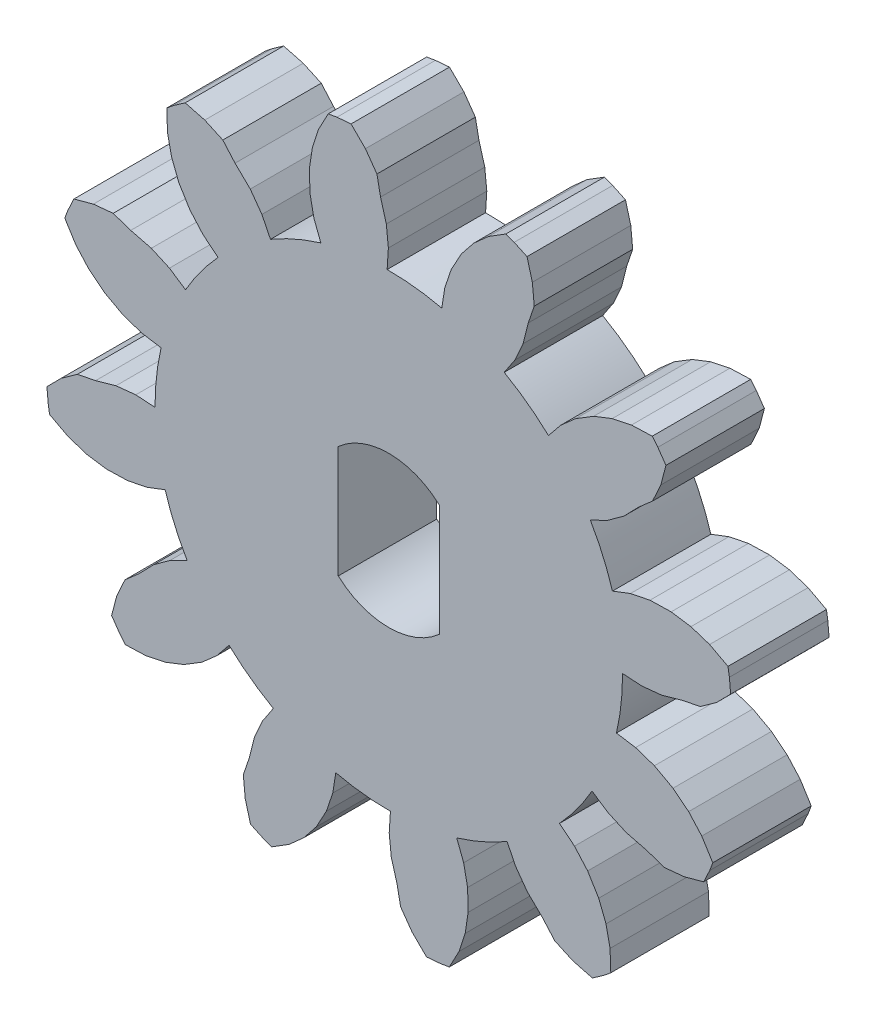
SolidWorks part; units mm, degrees
ref_plane "Front Plane" through (0, 0, 0) normal (0, 0, 1) x (1, 0, 0)
ref_plane "Top Plane" through (0, 0, 0) normal (0, 1, 0) x (1, 0, 0)
ref_plane "Right Plane" through (0, 0, 0) normal (1, 0, 0) x (0, 0, -1)
sketch "Sketch2" plane through (0, 0, 0) normal (0, 0, 1) x (1, 0, 0)
  line L0 (10.7643, 2.769) -> (11.3146, 2.9798)
  line L1 (11.3146, 2.9798) -> (11.9079, 3.1)
  line L2 (11.9079, 3.1) -> (12.5541, 3.1166)
  line L3 (12.5541, 3.1166) -> (13.1558, 3.0264)
  line L4 (13.1558, 3.0264) -> (13.7249, 2.84)
  line L5 (13.7249, 2.84) -> (14.2846, 2.5428)
  line L6 (14.2846, 2.5428) -> (14.3284, 2.2778)
  line L7 (10.8865, -0.9167) -> (11.4685, -1.0092)
  line L8 (14.3655, 1.8481) -> (14.3284, 2.2778)
  line L9 (13.9315, 1.41) -> (14.3655, 1.8481)
  line L10 (13.4388, 1.0592) -> (13.9315, 1.41)
  line L11 (12.8839, 0.949) -> (13.4388, 1.0592)
  line L12 (12.2621, 0.7727) -> (12.8839, 0.949)
  line L13 (11.6599, 0.7109) -> (12.2621, 0.7727)
  line L14 (11.0718, 0.7486) -> (11.6599, 0.7109)
  line L15 (11.4685, -1.0092) -> (12.0424, -1.2018)
  line L16 (12.0424, -1.2018) -> (12.6103, -1.5105)
  line L17 (12.6103, -1.5105) -> (13.0864, -1.8894)
  line L18 (13.0864, -1.8894) -> (13.486, -2.3355)
  line L19 (13.486, -2.3355) -> (13.8222, -2.8726)
  line L20 (13.8222, -2.8726) -> (13.7276, -3.1241)
  line L21 (13.5448, -3.5148) -> (13.7276, -3.1241)
  line L22 (12.9499, -3.6771) -> (13.5448, -3.5148)
  line L23 (12.3478, -3.7346) -> (12.9499, -3.6771)
  line L24 (11.8122, -3.5526) -> (12.3478, -3.7346)
  line L25 (11.1855, -3.3943) -> (11.8122, -3.5526)
  line L26 (10.6331, -3.1467) -> (11.1855, -3.3943)
  line L27 (10.1426, -2.8201) -> (10.6331, -3.1467)
  line L28 (9.1496, -4.1696) -> (9.6073, -4.5407)
  line L29 (9.6073, -4.5407) -> (10.008, -4.9945)
  line L30 (10.008, -4.9945) -> (10.3455, -5.5458)
  line L31 (10.3455, -5.5458) -> (10.5683, -6.112)
  line L32 (10.5683, -6.112) -> (10.6914, -6.6981)
  line L33 (10.6914, -6.6981) -> (10.7139, -7.3314)
  line L34 (10.7139, -7.3314) -> (10.5062, -7.5019)
  line L35 (10.1526, -7.7488) -> (10.5062, -7.5019)
  line L36 (9.5562, -7.5919) -> (10.1526, -7.7488)
  line L37 (9.0061, -7.3406) -> (9.5562, -7.5919)
  line L38 (8.6333, -6.9152) -> (9.0061, -7.3406)
  line L39 (8.1696, -6.4648) -> (8.6333, -6.9152)
  line L40 (7.815, -5.9742) -> (8.1696, -6.4648)
  line L41 (7.5536, -5.4461) -> (7.815, -5.9742)
  line L42 (6.0188, -6.1183) -> (6.2297, -6.6686)
  line L43 (6.2297, -6.6686) -> (6.3499, -7.2619)
  line L44 (6.3499, -7.2619) -> (6.3665, -7.908)
  line L45 (6.3665, -7.908) -> (6.2763, -8.5098)
  line L46 (6.2763, -8.5098) -> (6.0898, -9.0789)
  line L47 (6.0898, -9.0789) -> (5.7927, -9.6386)
  line L48 (5.7927, -9.6386) -> (5.5276, -9.6824)
  line L49 (5.098, -9.7194) -> (5.5276, -9.6824)
  line L50 (4.6599, -9.2854) -> (5.098, -9.7194)
  line L51 (4.3091, -8.7928) -> (4.6599, -9.2854)
  line L52 (4.1989, -8.2379) -> (4.3091, -8.7928)
  line L53 (4.0226, -7.616) -> (4.1989, -8.2379)
  line L54 (3.9608, -7.0138) -> (4.0226, -7.616)
  line L55 (3.9984, -6.4257) -> (3.9608, -7.0138)
  line L56 (2.3332, -6.2405) -> (2.2407, -6.8225)
  line L57 (2.2407, -6.8225) -> (2.0481, -7.3964)
  line L58 (2.0481, -7.3964) -> (1.7394, -7.9643)
  line L59 (1.7394, -7.9643) -> (1.3604, -8.4404)
  line L60 (1.3604, -8.4404) -> (0.9144, -8.84)
  line L61 (0.9144, -8.84) -> (0.3772, -9.1761)
  line L62 (0.3772, -9.1761) -> (0.1257, -9.0815)
  line L63 (-0.2649, -8.8988) -> (0.1257, -9.0815)
  line L64 (-0.4273, -8.3038) -> (-0.2649, -8.8988)
  line L65 (-0.4847, -7.7018) -> (-0.4273, -8.3038)
  line L66 (-0.3027, -7.1662) -> (-0.4847, -7.7018)
  line L67 (-0.1445, -6.5395) -> (-0.3027, -7.1662)
  line L68 (0.1031, -5.9871) -> (-0.1445, -6.5395)
  line L69 (0.4298, -5.4966) -> (0.1031, -5.9871)
  line L70 (-0.9197, -4.5036) -> (-1.2909, -4.9613)
  line L71 (-1.2909, -4.9613) -> (-1.7446, -5.362)
  line L72 (-1.7446, -5.362) -> (-2.2959, -5.6995)
  line L73 (-2.2959, -5.6995) -> (-2.8621, -5.9223)
  line L74 (-2.8621, -5.9223) -> (-3.4482, -6.0454)
  line L75 (-3.4482, -6.0454) -> (-4.0815, -6.0679)
  line L76 (-4.0815, -6.0679) -> (-4.252, -5.8602)
  line L77 (-4.4989, -5.5066) -> (-4.252, -5.8602)
  line L78 (-4.3421, -4.9102) -> (-4.4989, -5.5066)
  line L79 (-4.0908, -4.3601) -> (-4.3421, -4.9102)
  line L80 (-3.6654, -3.9872) -> (-4.0908, -4.3601)
  line L81 (-3.215, -3.5236) -> (-3.6654, -3.9872)
  line L82 (-2.7243, -3.169) -> (-3.215, -3.5236)
  line L83 (-2.1962, -2.9076) -> (-2.7243, -3.169)
  line L84 (-2.8684, -1.3728) -> (-3.4187, -1.5837)
  line L85 (-3.4187, -1.5837) -> (-4.012, -1.7038)
  line L86 (-4.012, -1.7038) -> (-4.6582, -1.7205)
  line L87 (-4.6582, -1.7205) -> (-5.2599, -1.6303)
  line L88 (-5.2599, -1.6303) -> (-5.829, -1.4438)
  line L89 (-5.829, -1.4438) -> (-6.3887, -1.1467)
  line L90 (-6.3887, -1.1467) -> (-6.4325, -0.8816)
  line L91 (-6.4696, -0.4519) -> (-6.4325, -0.8816)
  line L92 (-6.0356, -0.0138) -> (-6.4696, -0.4519)
  line L93 (-5.5429, 0.3369) -> (-6.0356, -0.0138)
  line L94 (-4.988, 0.4471) -> (-5.5429, 0.3369)
  line L95 (-4.3662, 0.6234) -> (-4.988, 0.4471)
  line L96 (-3.764, 0.6852) -> (-4.3662, 0.6234)
  line L97 (-3.1759, 0.6476) -> (-3.764, 0.6852)
  line L98 (-2.9906, 2.3128) -> (-3.5726, 2.4053)
  line L99 (-3.5726, 2.4053) -> (-4.1465, 2.5979)
  line L100 (-4.1465, 2.5979) -> (-4.7144, 2.9066)
  line L101 (-4.7144, 2.9066) -> (-5.1905, 3.2856)
  line L102 (-5.1905, 3.2856) -> (-5.5901, 3.7316)
  line L103 (-5.5901, 3.7316) -> (-5.9263, 4.2688)
  line L104 (-5.9263, 4.2688) -> (-5.8317, 4.5203)
  line L105 (-5.6489, 4.9109) -> (-5.8317, 4.5203)
  line L106 (-5.054, 5.0733) -> (-5.6489, 4.9109)
  line L107 (-4.4519, 5.1307) -> (-5.054, 5.0733)
  line L108 (-3.9163, 4.9487) -> (-4.4519, 5.1307)
  line L109 (-3.2896, 4.7905) -> (-3.9163, 4.9487)
  line L110 (-2.7372, 4.5429) -> (-3.2896, 4.7905)
  line L111 (-2.2467, 4.2163) -> (-2.7372, 4.5429)
  line L112 (-1.2537, 5.5658) -> (-1.7114, 5.9369)
  line L113 (-1.7114, 5.9369) -> (-2.1121, 6.3906)
  line L114 (-2.1121, 6.3906) -> (-2.4496, 6.9419)
  line L115 (-2.4496, 6.9419) -> (-2.6724, 7.5081)
  line L116 (-2.6724, 7.5081) -> (-2.7955, 8.0942)
  line L117 (-2.7955, 8.0942) -> (-2.818, 8.7275)
  line L118 (-2.818, 8.7275) -> (-2.6103, 8.898)
  line L119 (-2.2567, 9.1449) -> (-2.6103, 8.898)
  line L120 (-1.6603, 8.9881) -> (-2.2567, 9.1449)
  line L121 (-1.1102, 8.7368) -> (-1.6603, 8.9881)
  line L122 (-0.7374, 8.3114) -> (-1.1102, 8.7368)
  line L123 (-0.2737, 7.861) -> (-0.7374, 8.3114)
  line L124 (0.0809, 7.3703) -> (-0.2737, 7.861)
  line L125 (0.3423, 6.8422) -> (0.0809, 7.3703)
  line L126 (1.8771, 7.5144) -> (1.6662, 8.0647)
  line L127 (1.6662, 8.0647) -> (1.546, 8.658)
  line L128 (1.546, 8.658) -> (1.5294, 9.3042)
  line L129 (1.5294, 9.3042) -> (1.6196, 9.906)
  line L130 (1.6196, 9.906) -> (1.8061, 10.4751)
  line L131 (1.8061, 10.4751) -> (2.1032, 11.0347)
  line L132 (2.1032, 11.0347) -> (2.3683, 11.0786)
  line L133 (2.798, 11.1156) -> (2.3683, 11.0786)
  line L134 (3.236, 10.6816) -> (2.798, 11.1156)
  line L135 (3.5868, 10.1889) -> (3.236, 10.6816)
  line L136 (3.697, 9.634) -> (3.5868, 10.1889)
  line L137 (3.8733, 9.0122) -> (3.697, 9.634)
  line L138 (3.9351, 8.41) -> (3.8733, 9.0122)
  line L139 (3.8975, 7.8219) -> (3.9351, 8.41)
  line L140 (5.5627, 7.6367) -> (5.6552, 8.2186)
  line L141 (5.6552, 8.2186) -> (5.8478, 8.7926)
  line L142 (5.8478, 8.7926) -> (6.1565, 9.3605)
  line L143 (6.1565, 9.3605) -> (6.5355, 9.8365)
  line L144 (6.5355, 9.8365) -> (6.9815, 10.2361)
  line L145 (6.9815, 10.2361) -> (7.5187, 10.5723)
  line L146 (7.5187, 10.5723) -> (7.7702, 10.4777)
  line L147 (8.1608, 10.2949) -> (7.7702, 10.4777)
  line L148 (8.3232, 9.7) -> (8.1608, 10.2949)
  line L149 (8.3806, 9.098) -> (8.3232, 9.7)
  line L150 (8.1986, 8.5623) -> (8.3806, 9.098)
  line L151 (8.0404, 7.9356) -> (8.1986, 8.5623)
  line L152 (7.7928, 7.3832) -> (8.0404, 7.9356)
  line L153 (7.4661, 6.8927) -> (7.7928, 7.3832)
  line L154 (8.8156, 5.8997) -> (9.1868, 6.3574)
  line L155 (9.1868, 6.3574) -> (9.6405, 6.7582)
  line L156 (9.6405, 6.7582) -> (10.1918, 7.0957)
  line L157 (10.1918, 7.0957) -> (10.758, 7.3184)
  line L158 (10.758, 7.3184) -> (11.3441, 7.4415)
  line L159 (11.3441, 7.4415) -> (11.9774, 7.464)
  line L160 (11.9774, 7.464) -> (12.1479, 7.2564)
  line L161 (12.3948, 6.9028) -> (12.1479, 7.2564)
  line L162 (12.238, 6.3064) -> (12.3948, 6.9028)
  line L163 (11.9867, 5.7563) -> (12.238, 6.3064)
  line L164 (11.5613, 5.3834) -> (11.9867, 5.7563)
  line L165 (11.1109, 4.9198) -> (11.5613, 5.3834)
  line L166 (10.6202, 4.5652) -> (11.1109, 4.9198)
  line L167 (10.0921, 4.3037) -> (10.6202, 4.5652)
  line L171 (3.948, -1.6019) -> (3.948, 2.9981) construction
  line L174 (2.408, 0.6981) -> (2.408, -1.0103) construction
  line L175 (2.408, -1.0103) -> (2.408, 2.4064)
  line L176 (5.488, -1.0103) -> (5.488, 2.4064)
  arc A1 (-0.9197, -4.5036) -> (0.4298, -5.4966) centre (3.948, 0.6981) ccw
  arc A3 (2.408, -1.0103) -> (5.488, -1.0103) centre (3.948, 0.6981) ccw
  arc A4 (2.3332, -6.2405) -> (3.9984, -6.4257) centre (3.948, 0.6981) ccw
  arc A5 (6.0188, -6.1183) -> (7.5536, -5.4461) centre (3.948, 0.6981) ccw
  arc A6 (9.1496, -4.1696) -> (10.1426, -2.8201) centre (3.948, 0.6981) ccw
  arc A7 (10.8865, -0.9167) -> (11.0718, 0.7486) centre (3.948, 0.6981) ccw
  arc A8 (10.7643, 2.769) -> (10.0921, 4.3037) centre (3.948, 0.6981) ccw
  arc A9 (8.8156, 5.8997) -> (7.4661, 6.8927) centre (3.948, 0.6981) ccw
  arc A10 (5.5627, 7.6367) -> (3.8975, 7.8219) centre (3.948, 0.6981) ccw
  arc A11 (1.8771, 7.5144) -> (0.3423, 6.8422) centre (3.948, 0.6981) ccw
  arc A12 (-1.2537, 5.5658) -> (-2.2467, 4.2163) centre (3.948, 0.6981) ccw
  arc A13 (-2.9906, 2.3128) -> (-3.1759, 0.6476) centre (3.948, 0.6981) ccw
  arc A14 (-2.8684, -1.3728) -> (-2.1962, -2.9076) centre (3.948, 0.6981) ccw
  arc A15 (5.488, 2.4064) -> (2.408, 2.4064) centre (3.948, 0.6981) ccw
  point P195 (3.948, 0.6981)
  dimension "D1" = 12
  dimension "D2" = 1.54
  dimension "D3" = 14.248
extrude "Boss-Extrude1" add sketch "Sketch2" along normal blind 3
